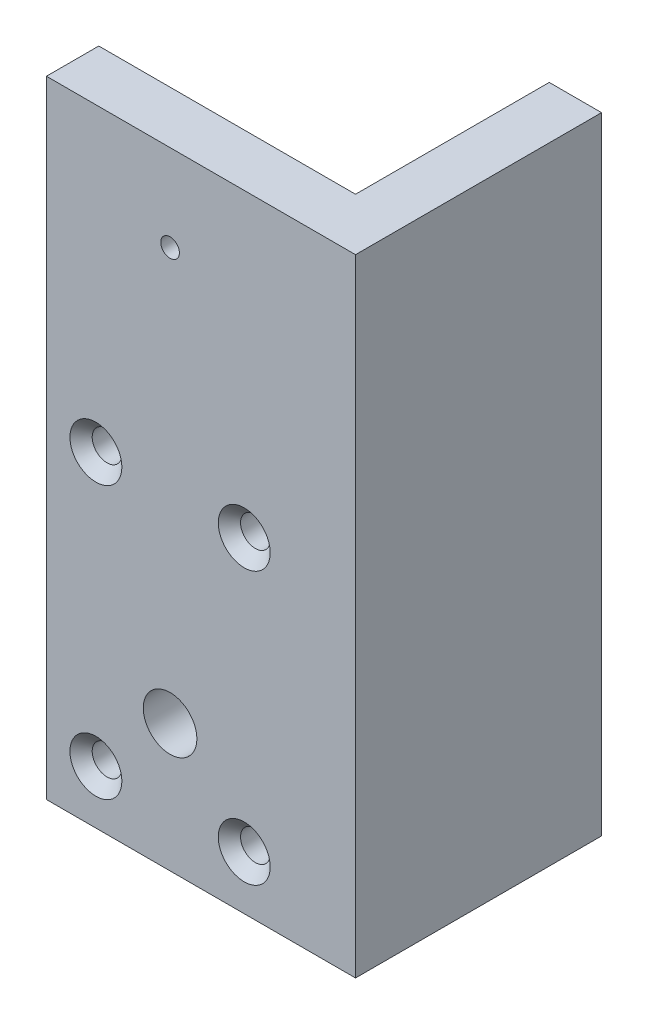
SolidWorks part; units mm, degrees
ref_plane "Front Plane" through (0, 0, 0) normal (0, 0, 1) x (1, 0, 0)
ref_plane "Top Plane" through (0, 0, 0) normal (0, 1, 0) x (1, 0, 0)
ref_plane "Right Plane" through (0, 0, 0) normal (1, 0, 0) x (0, 0, -1)
sketch "Sketch1" plane through (0, 0, 0) normal (0, 0, 1) x (1, 0, 0)
  line L1 (0, 0) -> (37.5, 0)
  line L2 (0, 0) -> (0, 46)
  line L3 (0, 46) -> (37.5, 46)
  line L4 (37.5, 0) -> (37.5, 46)
  circle A0 centre (6, 39.5) radius 1.7
  circle A1 centre (24, 39.5) radius 1.7
  circle A2 centre (24, 6.5) radius 1.7
  circle A3 centre (6, 6.5) radius 1.7
  circle A4 centre (15, 15.5) radius 3.25
  line B0 (30, 0) -> (0, 0)
  circle B1 centre (24, 39.5) radius 3.5
  circle B2 centre (6, 39.5) radius 3.5
  circle B3 centre (6, 6.5) radius 3.5
  circle B4 centre (24, 6.5) radius 3.5
  circle B5 centre (15, 15.5) radius 6.25
  dimension "D3" = 3.4
  dimension "D4" = 6.5
  dimension "D1" = 7.5
  dimension "D2" = 6.5
sketch_block_instance "DC_Motor_Mount-1"
sketch_block "DC_Motor_Mount"
extrude "Boss-Extrude1" add sketch "Sketch1" along normal blind 6.35 contours L1 L4 L3 L2 B5 B4 B3 B2 B1 | B5 A4 | B2 A0 | B1 A1 | B4 A2 | B3 A3
hole_wizard "CSK for M3 Flat Head Machine Screw1" positions "3DSketch1" profile "Sketch2" countersink size "M3" standard "ANSI Metric" end condition through all
sketch3d "3DSketch1"
  line L0 (6, 6.5, 6.35) -> (6, 6.5, 0) construction
  line L1 (6, 39.5, 6.35) -> (6, 39.5, 0) construction
  line L2 (24, 39.5, 6.35) -> (24, 39.5, 0) construction
  line L3 (24, 6.5, 6.35) -> (24, 6.5, 0) construction
  point P0 (6, 6.5, 6.35)
  point P4 (6, 39.5, 6.35)
  point P8 (24, 39.5, 6.35)
  point P12 (24, 6.5, 6.35)
sketch "Sketch2" plane through (6, 6.5, 6.35) normal (1, 0, 0) x (0, -1, 0)
  line L0 (0, 0) -> (0, 6.35)
  line L1 (0, 6.35) -> (1.8, 6.35)
  line L2 (1.8, 6.35) -> (1.8, 1.35)
  line L3 (1.8, 1.35) -> (3.15, 0)
  line L5 (3.15, 0) -> (0, 0)
  line L6 (-1.8, 1.35) -> (-3.15, 0) construction
  line L11 (0, -6.35) -> (0, 107.95) construction
  dimension "Thru Hole Dia." = 3.6
  dimension "Thru Hole Depth" = 6.35
  dimension "Near C'Sink Dia." = 6.3
  dimension "Near C'Sink Angle" = 90
sketch "Sketch3" plane through (0, 0, 0) normal (0, 0, -1) x (-1, 0, 0)
  line L0 (0, 46) -> (-37.5, 46) construction
  line L1 (-37.5, 0) -> (-31.15, 0)
  line L2 (-37.5, 0) -> (-37.5, 46)
  line L3 (-37.5, 46) -> (-31.15, 46)
  line L4 (-31.15, 0) -> (-31.15, 46)
  dimension "D1" = 6.35
extrude "Boss-Extrude2" add sketch "Sketch3" along normal blind 23.5
sketch "Sketch5" plane through (0, 46, 0) normal (0, 1, 0) x (1, 0, 0)
  line L6 (31.15, 0) -> (0, 0)
  line L7 (0, 0) -> (0, -6.35)
  line L8 (0, -6.35) -> (37.5, -6.35)
  line L9 (37.5, -6.35) -> (37.5, 23.5)
  line L10 (37.5, 23.5) -> (31.15, 23.5)
  line L11 (31.15, 23.5) -> (31.15, 0)
  line L12 (31.15, 0) -> (0, 0)
  line L13 (0, 0) -> (0, -6.35)
  line L14 (0, -6.35) -> (37.5, -6.35)
  line L15 (37.5, -6.35) -> (37.5, 23.5)
  line L16 (37.5, 23.5) -> (31.15, 23.5)
  line L17 (31.15, 23.5) -> (31.15, 0)
  dimension "D1" = 0
extrude "Boss-Extrude4" add sketch "Sketch5" along normal blind 30
sketch "Sketch6" plane through (0, 0, 6.35) normal (0, 0, 1) x (1, 0, 0)
  line L0 (15, 15.5) -> (15, 65.5) construction
  circle A0 centre (15, 65.5) radius 1.1303
  dimension "D1" = 2.2606
  dimension "D2" = 50
extrude "Cut-Extrude1" cut sketch "Sketch6" against normal up to next contours A0
sketch "Sketch7" plane through (0, 0, -23.5) normal (0, 0, -1) x (-1, 0, 0)
  line L0 (-34.325, 10) -> (-34.325, 66) construction
  line L1 (-34.325, 66) -> (-34.325, 76) construction
  line L2 (-37.5, 76) -> (-31.15, 76) construction
  line L3 (-34.325, 10) -> (-34.325, 0) construction
  line L4 (-37.5, 0) -> (-31.15, 0) construction
  circle A0 centre (-34.325, 10) radius 1.3891
  circle A1 centre (-34.325, 66) radius 1.3891
  dimension "D1" = 2.7781
  dimension "D2" = 10
extrude "Cut-Extrude2" cut sketch "Sketch7" against normal blind 10
sketch "Sketch8" plane through (0, 0, 6.35) normal (0, 0, 1) x (1, 0, 0)
  line L0 (37.5, 47.4219) -> (0, 47.4219)
  line L1 (34.325, 41.0719) -> (34.325, 6.7469) construction
  line L2 (34.325, 41.0719) -> (34.325, 47.4219) construction
  line L3 (34.325, 6.7469) -> (34.325, 0) construction
  line L4 (0, 0) -> (37.5, 0)
  line L5 (37.5, 0) -> (37.5, 76)
  line L6 (37.5, 76) -> (0, 76)
  line L7 (0, 76) -> (0, 0)
  line L8 (0, 0) -> (37.5, 0)
  line L9 (37.5, 0) -> (37.5, 47.4219)
  line L11 (0, 47.4219) -> (0, 0)
  line L13 (24, 6.5) -> (24, 0) construction
  circle A0 centre (6, 39.5) radius 1.8 construction
  circle A1 centre (6, 6.5) radius 1.8 construction
  circle A2 centre (24, 6.5) radius 1.8 construction
  circle A3 centre (24, 39.5) radius 1.8 construction
  circle A4 centre (6, 39.5) radius 1.8
  circle A5 centre (6, 6.5) radius 1.8
  circle A6 centre (24, 6.5) radius 1.8
  circle A7 centre (24, 39.5) radius 1.8
  circle A8 centre (34.325, 41.0719) radius 1.7859
  circle A9 centre (34.325, 6.7469) radius 1.7859
  circle A10 centre (15, 15.5) radius 3.25 construction
  circle A11 centre (15, 15.5) radius 3.25
  dimension "D4" = 3.5719
  dimension "D2" = 3.175
  dimension "D3" = 6.7469
  dimension "D5" = 34.325
  dimension "D6" = 6.35
  dimension "D1" = 0
